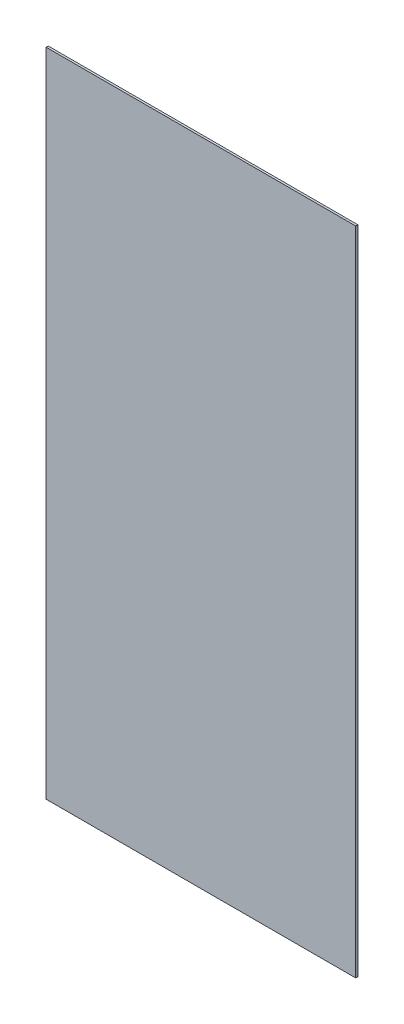
SolidWorks part; units mm, degrees
ref_plane "Front Plane" through (0, 0, 0) normal (0, 0, 1) x (1, 0, 0)
ref_plane "Top Plane" through (0, 0, 0) normal (0, 1, 0) x (1, 0, 0)
ref_plane "Right Plane" through (0, 0, 0) normal (1, 0, 0) x (0, 0, -1)
sketch "Sketch1" plane through (0, 0, 0) normal (0, 0, 1) x (1, 0, 0)
  line L1 (-145, 305) -> (145, 305)
  line L2 (-145, 305) -> (-145, -305)
  line L3 (-145, -305) -> (145, -305)
  line L4 (145, 305) -> (145, -305)
  line L5 (-145, 305) -> (145, -305) construction
  line L6 (-145, -305) -> (145, 305) construction
  point P0 (0, 0)
  dimension "D1" = 610
  dimension "D2" = 290
extrude "Boss-Extrude1" add sketch "Sketch1" along normal blind 2
